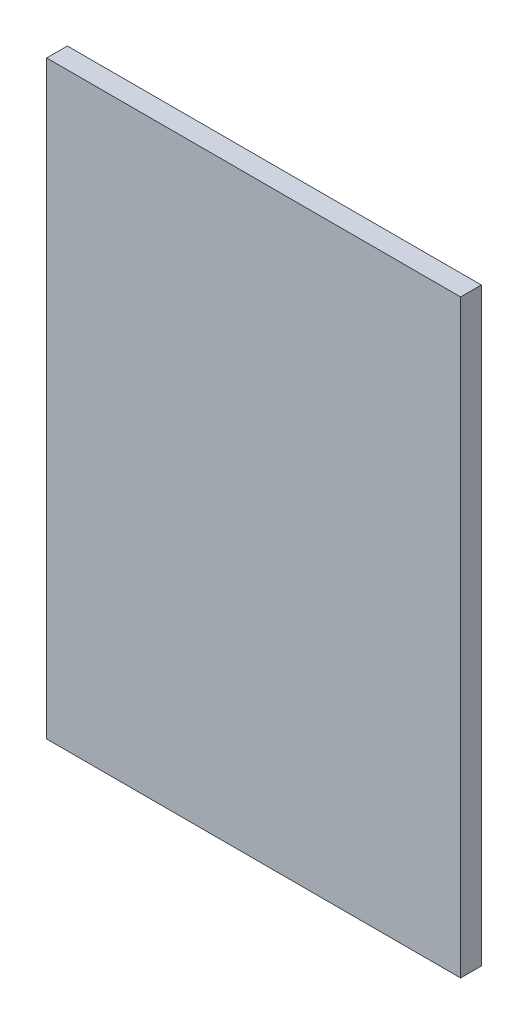
SolidWorks part; units mm, degrees
ref_plane "Front Plane" through (0, 0, 0) normal (0, 0, 1) x (1, 0, 0)
ref_plane "Top Plane" through (0, 0, 0) normal (0, 1, 0) x (1, 0, 0)
ref_plane "Right Plane" through (0, 0, 0) normal (1, 0, 0) x (0, 0, -1)
sketch "Sketch1" plane through (0, 0, 0) normal (0, 0, 1) x (1, 0, 0)
  line L1 (-127, -180.975) -> (127, -180.975)
  line L2 (-127, -180.975) -> (-127, 180.975)
  line L3 (-127, 180.975) -> (127, 180.975)
  line L4 (127, -180.975) -> (127, 180.975)
  line L5 (-127, -180.975) -> (127, 180.975) construction
  line L6 (-127, 180.975) -> (127, -180.975) construction
  point P0 (0, 0)
  dimension "D1" = 361.95
  dimension "D2" = 254
extrude "Boss-Extrude1" add sketch "Sketch1" along normal mid plane 12.7
